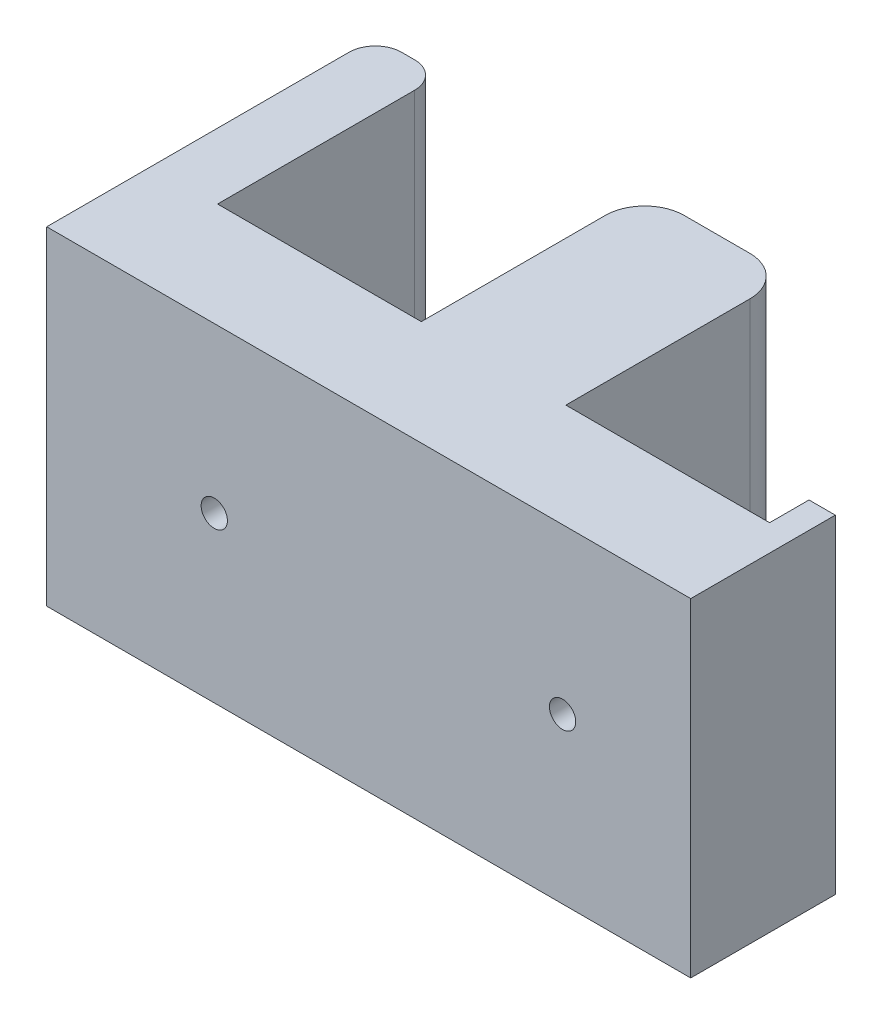
SolidWorks part; units mm, degrees
material "Pure Gold"
ref_plane "Front Plane" through (0, 0, 0) normal (0, 0, 1) x (1, 0, 0)
ref_plane "Top Plane" through (0, 0, 0) normal (0, 1, 0) x (1, 0, 0)
ref_plane "Right Plane" through (0, 0, 0) normal (1, 0, 0) x (0, 0, -1)
sketch "Sketch1" plane through (0, 0, 0) normal (0, 1, 0) x (1, 0, 0)
  line L0 (24.5, 0) -> (24.5, 25) construction
  line L1 (0, 0) -> (49, 0)
  line L2 (0, 0) -> (0, 25)
  line L3 (0, 25) -> (5, 25)
  line L4 (20.5, 25) -> (31.5, 25)
  line L5 (5, 25) -> (5, 8)
  line L6 (5, 8) -> (20.5, 8)
  line L7 (20.5, 8) -> (20.5, 25)
  line L8 (31.5, 25) -> (31.5, 8)
  line L9 (31.5, 8) -> (47, 8)
  line L10 (47, 8) -> (47, 11)
  line L11 (47, 11) -> (49, 11)
  line L12 (49, 11) -> (49, 0)
  dimension "D1" = 49
  dimension "D2" = 2
  dimension "D3" = 17
  dimension "D5" = 15.5
  dimension "D6" = 17
  dimension "D7" = 11
  dimension "D8" = 15.5
  dimension "D9" = 3
extrude "Boss-Extrude1" add sketch "Sketch1" along normal blind 25
fillet "Fillet2" radius 3 2 edges at (20.5, 12.5, -25) (31.5, 12.5, -25)
fillet "Fillet3" radius 2 2 edges at (0, 12.5, -25) (5, 12.5, -25)
sketch "Sketch3" plane through (0, 0, -8) normal (0, 0, -1) x (-1, 0, 0)
  line L0 (-39.25, 25) -> (-39.25, 0) construction
  line L1 (-31.5, 25) -> (-47, 25) construction
  line L2 (-31.5, 0) -> (-47, 0) construction
  line L3 (-47, 12.5) -> (-31.5, 12.5) construction
  line L4 (-47, 25) -> (-47, 0) construction
  line L5 (-31.5, 25) -> (-31.5, 0) construction
  line L6 (-12.75, 25) -> (-12.75, 0) construction
  line L7 (-5, 25) -> (-20.5, 25) construction
  line L8 (-5, 0) -> (-20.5, 0) construction
  line L9 (-20.5, 12.5) -> (-5, 12.5) construction
  line L10 (-20.5, 25) -> (-20.5, 0) construction
  line L11 (-5, 25) -> (-5, 0) construction
  circle A0 centre (-39.25, 12.5) radius 1
  circle A1 centre (-12.75, 12.5) radius 1
  dimension "D1" = 2
  dimension "D2" = 2
extrude "Cut-Extrude1" cut sketch "Sketch3" against normal through all
